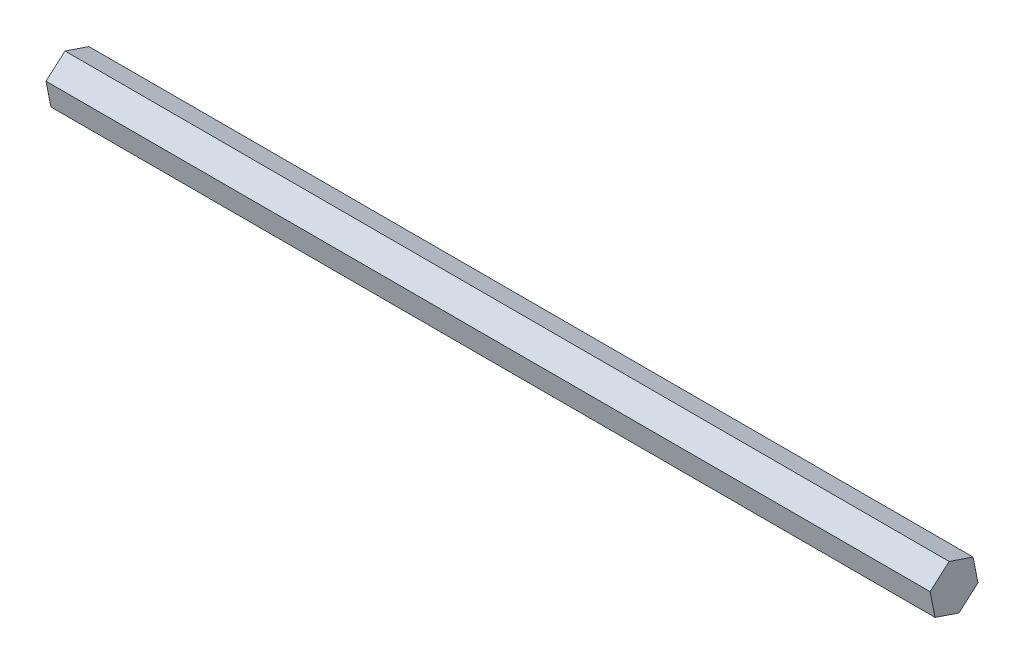
SolidWorks part; units mm, degrees
ref_plane "Front Plane" through (0, 0, 0) normal (0, 0, 1) x (1, 0, 0)
ref_plane "Top Plane" through (0, 0, 0) normal (0, 1, 0) x (1, 0, 0)
ref_plane "Right Plane" through (0, 0, 0) normal (1, 0, 0) x (0, 0, -1)
sketch "Sketch3" plane through (0, 0, 0) normal (1, 0, 0) x (0, 0, -1)
  line L1 (5.5135, 4.8337) -> (-1.4294, 7.1917)
  line L2 (-1.4294, 7.1917) -> (-6.9429, 2.3579)
  line L3 (-6.9429, 2.3579) -> (-5.5135, -4.8337)
  line L4 (-5.5135, -4.8337) -> (1.4294, -7.1917)
  line L5 (1.4294, -7.1917) -> (6.9429, -2.3579)
  line L6 (6.9429, -2.3579) -> (5.5135, 4.8337)
  circle A0 centre (0, 0) radius 6.35 construction
  dimension "D1" = 12.7
extrude "Boss-Extrude1" add sketch "Sketch3" along normal blind 256.54
